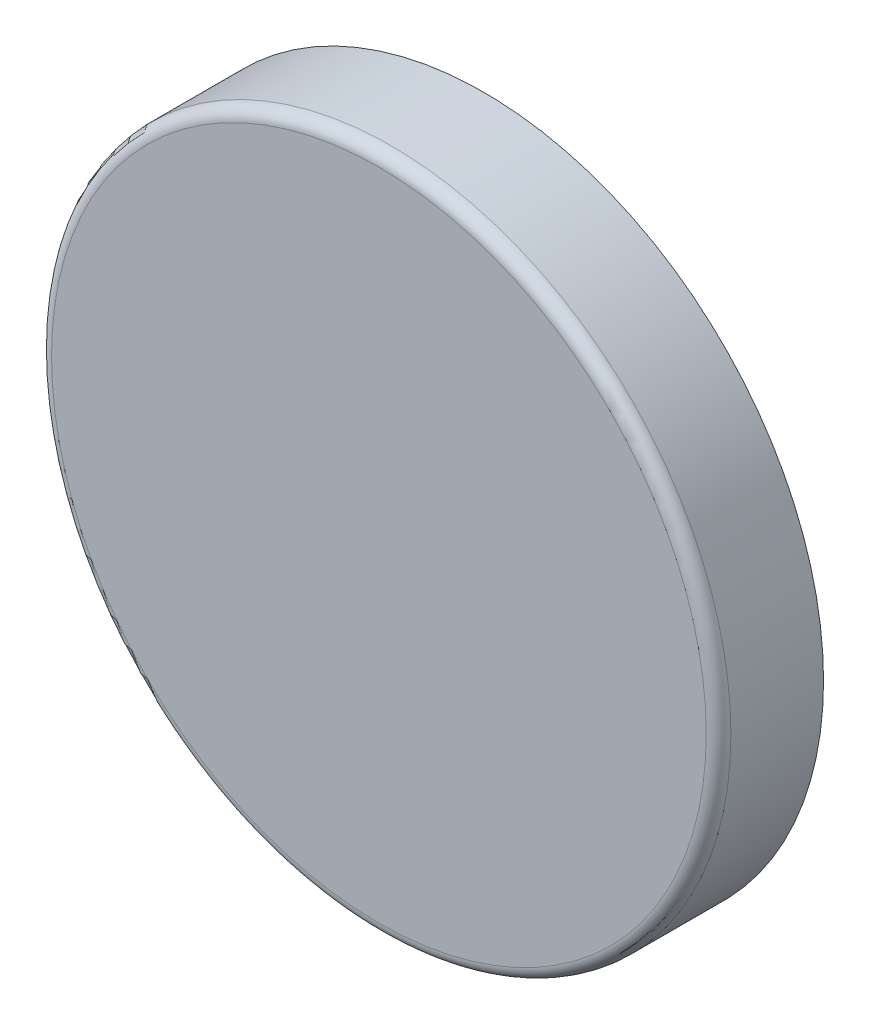
SolidWorks part; units mm, degrees
ref_plane "Front Plane" through (0, 0, 0) normal (0, 0, 1) x (1, 0, 0)
ref_plane "Top Plane" through (0, 0, 0) normal (0, 1, 0) x (1, 0, 0)
ref_plane "Right Plane" through (0, 0, 0) normal (1, 0, 0) x (0, 0, -1)
sketch "Sketch1" plane through (0, 0, 1312.0165) normal (0, 0, 1) x (1, 0, 0)
  circle A2 centre (907.549, 1390.8266) radius 55 construction
  circle A3 centre (907.549, 1390.8266) radius 55
extrude "Boss-Extrude1" add sketch "Sketch1" along normal blind 17
fillet "Fillet1" radius 2 1 edges at (962.549, 1390.8266, 1329.0165)
